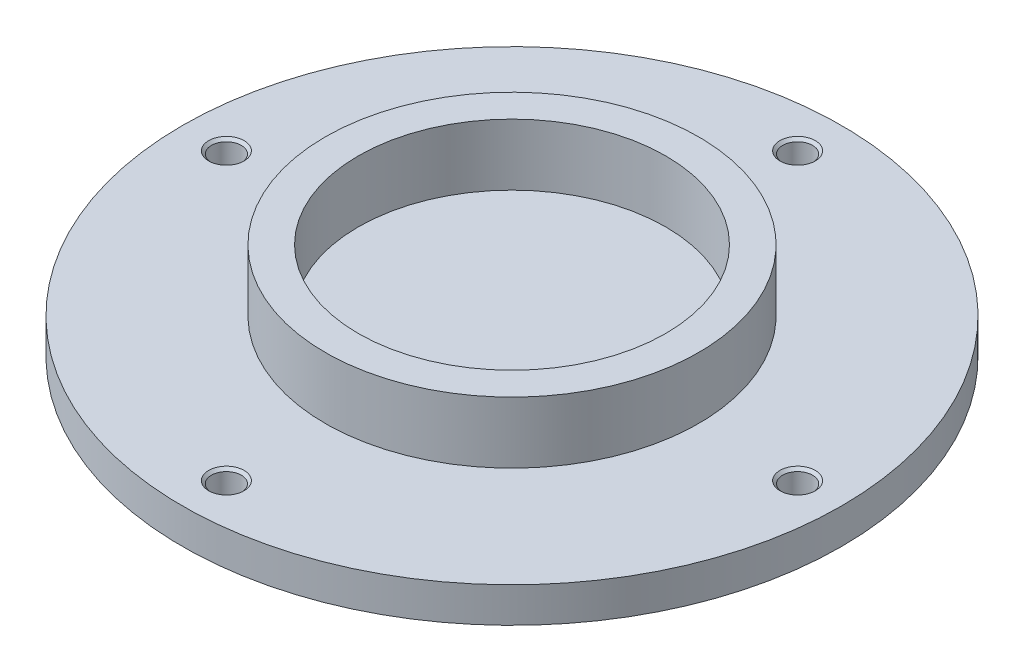
SolidWorks part; units mm, degrees
ref_plane "前视基准面" through (0, 0, 0) normal (0, 0, 1) x (1, 0, 0)
ref_plane "上视基准面" through (0, 0, 0) normal (0, 1, 0) x (1, 0, 0)
ref_plane "右视基准面" through (0, 0, 0) normal (1, 0, 0) x (0, 0, -1)
other "Configuration Table"
sketch "草图1" plane through (0, 0, 0) normal (0, 0, 1) x (1, 0, 0)
  line L0 (0, 34.8163) -> (0, -25.9388) construction
  line L1 (0, 0) -> (75, 0)
  line L2 (75, 0) -> (75, 8)
  line L3 (75, 8) -> (42.5, 8)
  line L4 (42.5, 8) -> (42.5, 22)
  line L5 (42.5, 22) -> (35, 22)
  line L6 (35, 22) -> (35, 8)
  line L7 (35, 8) -> (0, 8)
  line L8 (0, 8) -> (0, 0)
  dimension "D1" = 7.5
  dimension "D2" = 75
  dimension "D3" = 8
  dimension "D4" = 35
  dimension "D5" = 14
revolve "旋转1" add sketch "草图1" angle 360 about L8
sketch "草图2" plane through (0, 0, 0) normal (0, 1, 0) x (1, 0, 0)
  circle A0 centre (0, 0) radius 65
  circle A1 centre (65, 0) radius 4.5
  circle A2 centre (0, -65) radius 4.5
  circle A3 centre (-65, 0) radius 4.5
  circle A4 centre (0, 65) radius 4.5
  point P14 (0, 0)
  dimension "D1" = 4
  dimension "D2" = 130
hole_wizard "M8 螺纹孔1" positions "草图7" profile "草图8" tap size "M8" standard "GB" end condition through all
sketch "草图7" plane through (0, 8, 0) normal (0, 1, 0) x (1, 0, 0)
  point P0 (-65, 0)
  point P3 (65, 0)
  point P6 (0, -65)
  point P9 (0, 65)
sketch "草图8" plane through (-65, 8, 0) normal (1, 0, 0) x (0, 0, 1)
  line L0 (0, 0) -> (0, 8)
  line L1 (0, 8) -> (3.4, 8)
  line L2 (3.4, 8) -> (3.4, 0.625)
  line L3 (3.4, 0.625) -> (4.025, 0)
  line L5 (4.025, 0) -> (0, 0)
  line L6 (-3.4, 0.625) -> (-4.025, 0) construction
  line L11 (0, -6.35) -> (0, 107.95) construction
  dimension "通孔螺纹孔钻头直径" = 6.8
  dimension "通孔螺纹孔钻头深度" = 8
  dimension "近端锥形沉头孔直径" = 8.05
  dimension "近端锥形沉头孔角度" = 90
cosmetic thread "孔螺蚊线1"
cosmetic thread "孔螺蚊线2"
cosmetic thread "孔螺蚊线3"
cosmetic thread "孔螺蚊线4"
sketch "草图3" plane through (0, 0, 0) normal (0, 1, 0) x (1, 0, 0)
  circle A0 centre (0, 0) radius 21
sketch "草图4" plane through (0, 0, 0) normal (1, 0, 0) x (0, 0, -1)
  line L0 (0, 0) -> (0, 4)
  line L1 (0, 4) -> (10.5, 4)
  line L2 (25.5, 4) -> (25.5, 1)
  line L3 (25.5, 1) -> (21, 1)
  line L5 (21, 7) -> (25.5, 7)
  line L6 (25.5, 7) -> (25.5, 4)
  line L7 (0, 0) -> (0, 13.0193) construction
  line L8 (21, 7) -> (10.5, 7)
  line L9 (0, 7) -> (0, 1)
  line L10 (10.5, 7) -> (10.5, 1)
  line L11 (10.5, 1) -> (21, 1)
